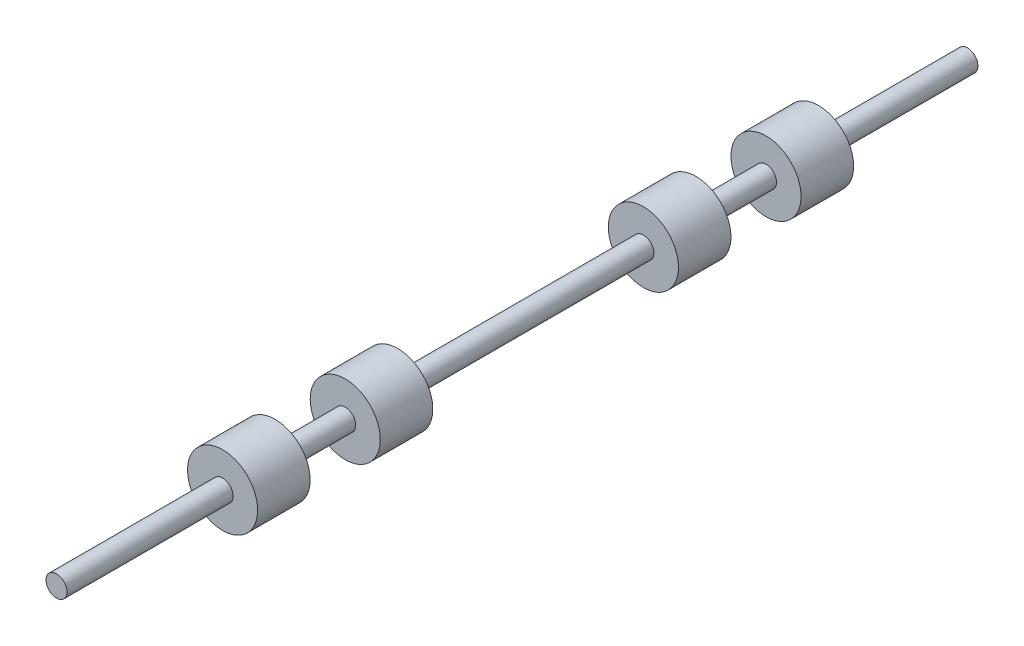
SolidWorks part; units mm, degrees
ref_plane "Front Plane" through (0, 0, 0) normal (0, 0, 1) x (1, 0, 0)
ref_plane "Top Plane" through (0, 0, 0) normal (0, 1, 0) x (1, 0, 0)
ref_plane "Right Plane" through (0, 0, 0) normal (1, 0, 0) x (0, 0, -1)
sketch "Sketch1" plane through (0, 0, 0) normal (0, 0, 1) x (1, 0, 0)
  circle A0 centre (0, 0) radius 7.62
  dimension "D1" = 15.24
extrude "Boss-Extrude1" add sketch "Sketch1" along normal blind 660.4
sketch "Sketch2" plane through (0, 0, 0) normal (0, 1, 0) x (1, 0, 0)
  line L0 (0, 0) -> (0, -660.4) construction
  line L1 (-7.62, -660.4) -> (7.62, -660.4) construction
  line L2 (0, -476.504) -> (70.3581, -476.504) construction
  line L3 (0, -107.95) -> (25.4, -107.95)
  line L4 (0, -107.95) -> (0, -146.05)
  line L5 (0, -146.05) -> (25.4, -146.05)
  line L6 (25.4, -107.95) -> (25.4, -146.05)
  line L7 (0, -196.85) -> (25.4, -196.85)
  line L8 (0, -196.85) -> (0, -234.95)
  line L9 (0, -234.95) -> (25.4, -234.95)
  line L10 (25.4, -196.85) -> (25.4, -234.95)
  line L11 (0, -451.104) -> (25.4, -451.104)
  line L12 (0, -451.104) -> (0, -413.004)
  line L13 (0, -413.004) -> (25.4, -413.004)
  line L14 (25.4, -451.104) -> (25.4, -413.004)
  line L15 (0, -540.004) -> (25.4, -540.004)
  line L16 (0, -540.004) -> (0, -501.904)
  line L17 (0, -501.904) -> (25.4, -501.904)
  line L18 (25.4, -540.004) -> (25.4, -501.904)
  line L19 (0, -171.45) -> (84.0331, -171.45) construction
  dimension "D1" = 25.4
  dimension "D2" = 38.1
  dimension "D3" = 25.4
  dimension "D4" = 38.1
  dimension "D5" = 50.8
  dimension "D6" = 25.4
  dimension "D7" = 25.4
  dimension "D8" = 38.1
  dimension "D9" = 38.1
  dimension "D10" = 183.896
  dimension "D11" = 305.054
  dimension "D12" = 50.8
revolve "Revolve1" add sketch "Sketch2" angle 360 about L0
